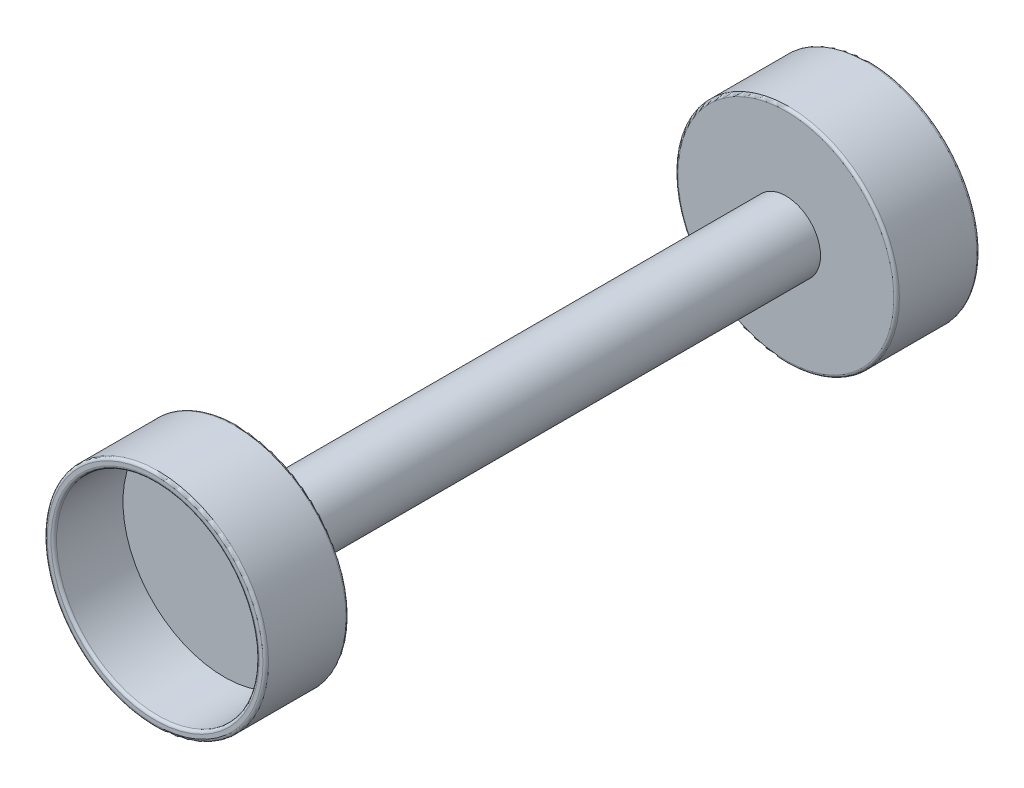
SolidWorks part; units mm, degrees
material "ABS"
ref_plane "Front Plane" through (0, 0, 0) normal (0, 0, 1) x (1, 0, 0)
ref_plane "Top Plane" through (0, 0, 0) normal (0, 1, 0) x (1, 0, 0)
ref_plane "Right Plane" through (0, 0, 0) normal (1, 0, 0) x (0, 0, -1)
sketch "Sketch4" plane through (0, 0, 0) normal (0, 0, 1) x (1, 0, 0)
  circle A0 centre (0, 0) radius 31.75
  dimension "D1" = 63.5
extrude "Boss-Extrude3" add sketch "Sketch4" along normal mid plane 502.92
sketch "Sketch5" plane through (0, 0, 251.46) normal (0, 0, 1) x (1, 0, 0)
  circle A0 centre (0, 0) radius 101.6
  dimension "D1" = 203.2
extrude "Boss-Extrude4" add sketch "Sketch5" along normal blind 76.2
sketch "Sketch6" plane through (0, 0, 327.66) normal (0, 0, 1) x (1, 0, 0)
  circle A0 centre (0, 0) radius 92.964
  dimension "D1" = 185.928
extrude "Cut-Extrude1" cut sketch "Sketch6" against normal blind 63.5
fillet "Fillet1" radius 2.54 1 edges at (92.964, 0, 327.66)
fillet "Fillet2" radius 2.54 2 edges at (101.6, 0, 251.46) (101.6, 0, 327.66)
mirror "Mirror1" about plane through (0, 0, 0) normal (0, 0, 1) of "Boss-Extrude4", "Cut-Extrude1", "Fillet1", "Fillet2"
